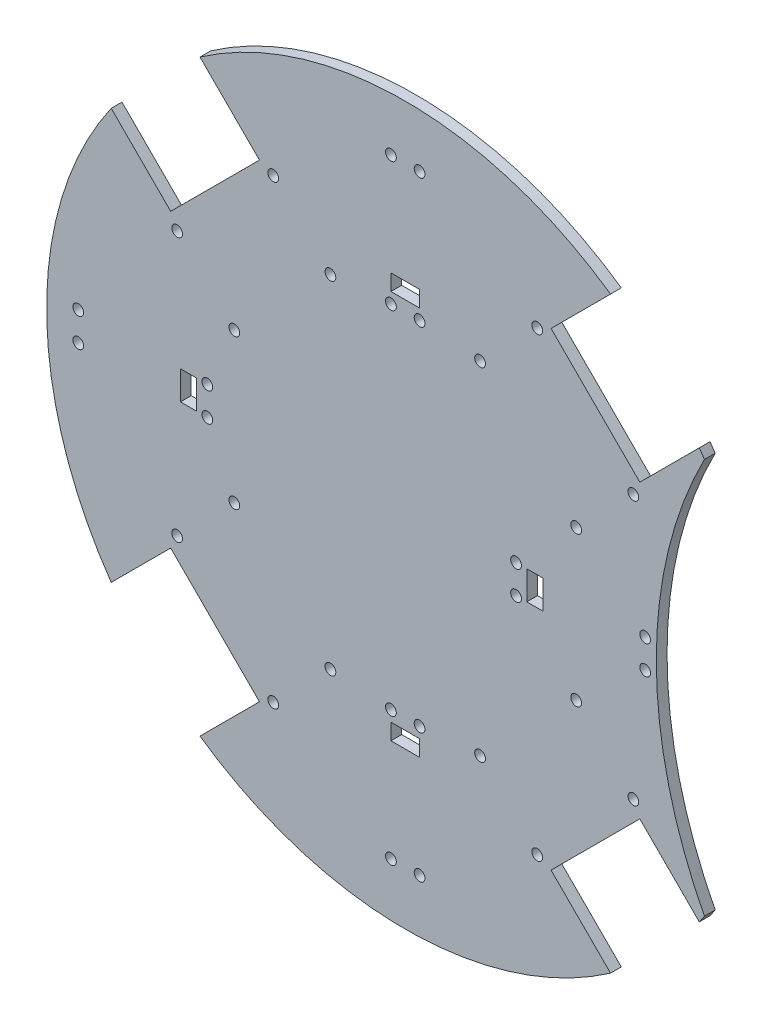
SolidWorks part; units mm, degrees
ref_plane "Alzado" through (0, 0, 0) normal (0, 0, 1) x (1, 0, 0)
ref_plane "Planta" through (0, 0, 0) normal (0, 1, 0) x (1, 0, 0)
ref_plane "Vista lateral" through (0, 0, 0) normal (1, 0, 0) x (0, 0, -1)
sketch "Croquis1" plane through (0, 0, 0) normal (0, 0, 1) x (1, 0, 0)
  circle A0 centre (0, 0) radius 100
  dimension "D1" = 200
extrude "Saliente-Extruir1" add sketch "Croquis1" along normal blind 3
sketch "Croquis3" plane through (0, 0, 3) normal (0, 0, 1) x (1, 0, 0)
  line L0 (0, 0) -> (190, 0) construction
  circle A0 centre (190, 0) radius 120
  dimension "D1" = 240
  dimension "D2" = 190
extrude "Cortar-Extruir1" cut sketch "Croquis3" against normal blind 3
sketch "Croquis5" plane through (0, 0, 3) normal (0, 0, 1) x (1, 0, 0)
  line L0 (0, -100) -> (0, 100) construction
  line L1 (-100, 0) -> (70, 0) construction
  line L2 (0, 0) -> (-70.7107, -70.7107) construction
  line L3 (-70.7107, -70.7107) -> (70.7107, 70.7107) construction
  line L4 (0, 0) -> (-70.7107, 70.7107) construction
  line L5 (-70.7107, 70.7107) -> (70.7107, -70.7107) construction
  line L6 (-70.7107, -70.7107) -> (-58.3363, -83.085) construction
  line L9 (-58.3363, -83.085) -> (-83.085, -58.3363)
  line L11 (-83.085, -58.3363) -> (-65.4074, -40.6586)
  line L12 (-65.4074, -40.6586) -> (-40.6586, -65.4074)
  line L13 (-40.6586, -65.4074) -> (-58.3363, -83.085)
  line L14 (-70.7107, 70.7107) -> (-83.085, 58.3363) construction
  line L15 (-83.085, 58.3363) -> (-100, 0) construction
  line L17 (-83.085, 58.3363) -> (-58.3363, 83.085)
  line L18 (-58.3363, 83.085) -> (-40.6586, 65.4074)
  line L19 (-40.6586, 65.4074) -> (-65.4074, 40.6586)
  line L20 (-65.4074, 40.6586) -> (-83.085, 58.3363)
  line L22 (70.7107, -70.7107) -> (58.3363, -83.085) construction
  line L23 (58.3363, -83.085) -> (0, -100) construction
  line L24 (58.3363, -83.085) -> (83.085, -58.3363)
  line L25 (83.085, -58.3363) -> (65.4074, -40.6586)
  line L26 (65.4074, -40.6586) -> (40.6586, -65.4074)
  line L27 (40.6586, -65.4074) -> (58.3363, -83.085)
  line L28 (70.7107, 70.7107) -> (58.3363, 83.085) construction
  line L29 (58.3363, 83.085) -> (0, 100) construction
  line L30 (58.3363, 83.085) -> (83.085, 58.3363)
  line L31 (83.085, 58.3363) -> (65.4074, 40.6586)
  line L32 (65.4074, 40.6586) -> (40.6586, 65.4074)
  line L33 (40.6586, 65.4074) -> (58.3363, 83.085)
  arc A0 (83.4211, 55.1446) -> (83.4211, -55.1446) centre (0, 0) ccw construction
  arc A1 (83.4211, 55.1446) -> (83.4211, -55.1446) centre (190, 0) ccw construction
  point P36 (0, 0)
  dimension "D2" = 17.5
  dimension "D3" = 25
  dimension "D4" = 35
  dimension "D5" = 25
  dimension "D6" = 35
  dimension "D8" = 25
  dimension "D9" = 17.5
  dimension "D7" = 35
  dimension "D10" = 90
  dimension "D11" = 17.5
  dimension "D12" = 17.5
  dimension "D13" = 35
  dimension "D14" = 25
  dimension "D15" = 134.3503
  dimension "D16" = 100
extrude "Cortar-Extruir6" cut sketch "Croquis5" against normal blind 10
sketch "Croquis12" plane through (0, 0, 3) normal (0, 0, 1) x (1, 0, 0)
  line L0 (-53.033, -53.033) -> (-39.9421, -50.0116) construction
  line L1 (-40.6586, -65.4074) -> (-65.4074, -40.6586) construction
  line L2 (-39.9421, -50.0116) -> (-36.8049, -63.6043) construction
  line L3 (-36.8049, -63.6043) -> (-63.6043, -36.8049) construction
  line L4 (-63.6043, -36.8049) -> (-47.6661, -20.8667) construction
  line L6 (53.033, -53.033) -> (-53.033, 53.033) construction
  line L7 (65.4074, -40.6586) -> (40.6586, -65.4074) construction
  line L8 (-65.4074, 40.6586) -> (-40.6586, 65.4074) construction
  line L9 (36.8049, 63.6043) -> (20.8667, 47.6661) construction
  line L10 (63.6043, 36.8049) -> (36.8049, 63.6043) construction
  line L11 (50.0116, 39.9421) -> (63.6043, 36.8049) construction
  line L12 (53.033, 53.033) -> (50.0116, 39.9421) construction
  line L14 (53.033, -53.033) -> (50.2046, -50.2046) construction
  line L15 (50.2046, -50.2046) -> (36.8049, -63.6043) construction
  line L16 (36.8049, -63.6043) -> (63.6043, -36.8049) construction
  line L17 (63.6043, -36.8049) -> (47.6661, -20.8667) construction
  line L19 (-53.033, -53.033) -> (53.033, 53.033) construction
  line L20 (-36.8049, 63.6043) -> (-20.8667, 47.6661) construction
  line L21 (-63.6043, 36.8049) -> (-36.8049, 63.6043) construction
  line L22 (-50.2046, 50.2046) -> (-63.6043, 36.8049) construction
  line L23 (-53.033, 53.033) -> (-50.2046, 50.2046) construction
  circle A0 centre (-63.6043, -36.8049) radius 1.5
  circle A1 centre (-36.8049, -63.6043) radius 1.5
  circle A2 centre (-47.6661, -20.8667) radius 1.5
  circle A3 centre (-20.8667, -47.6661) radius 1.5
  circle A5 centre (47.6661, 20.8667) radius 1.5
  circle A6 centre (20.8667, 47.6661) radius 1.5
  circle A7 centre (63.6043, 36.8049) radius 1.5
  circle A8 centre (36.8049, 63.6043) radius 1.5
  circle A10 centre (20.8667, -47.6661) radius 1.5
  circle A11 centre (47.6661, -20.8667) radius 1.5
  circle A12 centre (63.6043, -36.8049) radius 1.5
  circle A13 centre (36.8049, -63.6043) radius 1.5
  circle A15 centre (-63.6043, 36.8049) radius 1.5
  circle A16 centre (-36.8049, 63.6043) radius 1.5
  circle A17 centre (-20.8667, 47.6661) radius 1.5
  circle A18 centre (-47.6661, 20.8667) radius 1.5
  dimension "D2" = 3
  dimension "D3" = 3
  dimension "D4" = 4
  dimension "D5" = 4
  dimension "D6" = 3
  dimension "D7" = 3
  dimension "D8" = 37.9
  dimension "D9" = 22.54
  dimension "D10" = 22.54
  dimension "D11" = 37.9
  dimension "D12" = 18.95
  dimension "D13" = 18.95
  dimension "D14" = 3
  dimension "D15" = 3
  dimension "D16" = 3
  dimension "D17" = 3
  dimension "D18" = 37.9
  dimension "D19" = 22.54
  dimension "D20" = 22.54
  dimension "D21" = 37.9
  dimension "D22" = 4
  dimension "D1" = 13.95
extrude "Cortar-Extruir7" cut sketch "Croquis12" against normal through all
sketch "Croquis9" plane through (0, 0, 3) normal (0, 0, 1) x (1, 0, 0)
  line L0 (0, 0) -> (-100, 0) construction
  line L5 (0, 100) -> (0, -100) construction
  line L6 (33.9, 4) -> (38.4, 4)
  line L7 (33.9, 4) -> (33.9, -4)
  line L8 (33.9, -4) -> (38.4, -4)
  line L9 (38.4, 4) -> (38.4, -4)
  line L10 (-4, -52) -> (4, -52)
  line L11 (-58.1901, 4) -> (-62.6901, 4)
  line L12 (-58.1901, 4) -> (-58.1901, -4)
  line L13 (-58.1901, -4) -> (-62.6901, -4)
  line L14 (-62.6901, 4) -> (-62.6901, -4)
  line L15 (-4, 56.5) -> (4, 56.5)
  line L16 (-4, 56.5) -> (-4, 52)
  line L17 (-4, 52) -> (4, 52)
  line L18 (4, 56.5) -> (4, 52)
  line L19 (4, -56.5) -> (4, -52)
  line L20 (-4, -56.5) -> (4, -56.5)
  line L21 (-4, -56.5) -> (-4, -52)
  line L22 (0, 0) -> (70, 0) construction
  line L24 (-58.2511, -4) -> (-58.2738, -4) construction
  circle A0 centre (66.9, -4) radius 1.5
  circle A1 centre (30.9, 4) radius 1.5
  circle A4 centre (66.9, 4) radius 1.5
  circle A5 centre (30.9, -4) radius 1.5
  arc A6 (-81.9939, 57.2451) -> (-81.9939, -57.2451) centre (0, 0) ccw construction
  arc A7 (83.4211, 55.1446) -> (83.4211, -55.1446) centre (190, 0) ccw construction
  circle A8 centre (-91.1901, 4) radius 1.5
  circle A9 centre (-91.1901, -4) radius 1.5
  circle A10 centre (-55.1901, 4) radius 1.5
  circle A11 centre (-55.1901, -4) radius 1.5
  circle A12 centre (-4, 85) radius 1.5
  circle A13 centre (4, 85) radius 1.5
  circle A14 centre (-4, 49) radius 1.5
  circle A15 centre (4, 49) radius 1.5
  circle A20 centre (-4, -49) radius 1.5
  circle A21 centre (4, -49) radius 1.5
  circle A22 centre (4, -85) radius 1.5
  circle A23 centre (-4, -85) radius 1.5
  arc A25 (57.2451, 81.9939) -> (-57.2451, 81.9939) centre (0, 0) ccw construction
  dimension "D6" = 30.9
  dimension "D7" = 3
  dimension "D8" = 36
  dimension "D9" = 36
  dimension "D10" = 3
  dimension "D11" = 3
  dimension "D12" = 4
  dimension "D13" = 4
  dimension "D14" = 3
  dimension "D15" = 3
  dimension "D16" = 3
  dimension "D21" = 4
  dimension "D22" = 4
  dimension "D23" = 3
  dimension "D24" = 3
  dimension "D25" = 4
  dimension "D26" = 4
  dimension "D27" = 36
  dimension "D28" = 36
  dimension "D29" = 91.1901
  dimension "D30" = 91.1901
  dimension "D35" = 3
  dimension "D36" = 3
  dimension "D37" = 8
  dimension "D38" = 4
  dimension "D39" = 3
  dimension "D40" = 3
  dimension "D41" = 8
  dimension "D42" = 36
  dimension "D43" = 36
  dimension "D44" = 36
  dimension "D45" = 4
  dimension "D46" = 4
  dimension "D51" = 4
  dimension "D52" = 4
  dimension "D53" = 30.9
  dimension "D55" = 36
  dimension "D56" = 49
  dimension "D57" = 49
  dimension "D58" = 3
  dimension "D59" = 3
  dimension "D60" = 3
  dimension "D61" = 3
  dimension "D62" = 4.5
  dimension "D32" = 8
  dimension "D64" = 0
  dimension "D69" = 8
  dimension "D70" = 4
  dimension "D71" = 85.0941
  dimension "D72" = 85.0941
  dimension "D17" = 4.5
  dimension "D18" = 8
  dimension "D19" = 3
  dimension "D20" = 0
  dimension "D31" = 3.061
  dimension "D33" = 3
  dimension "D34" = 0
  dimension "D47" = 8
  dimension "D48" = 4.5
  dimension "D49" = 0
  dimension "D50" = 3
  dimension "D54" = 4
  dimension "D63" = 0
  dimension "D65" = 3
  dimension "D66" = 4.5
  dimension "D67" = 8
  dimension "D68" = 3
extrude "Cortar-Extruir5" cut sketch "Croquis9" against normal blind 10
